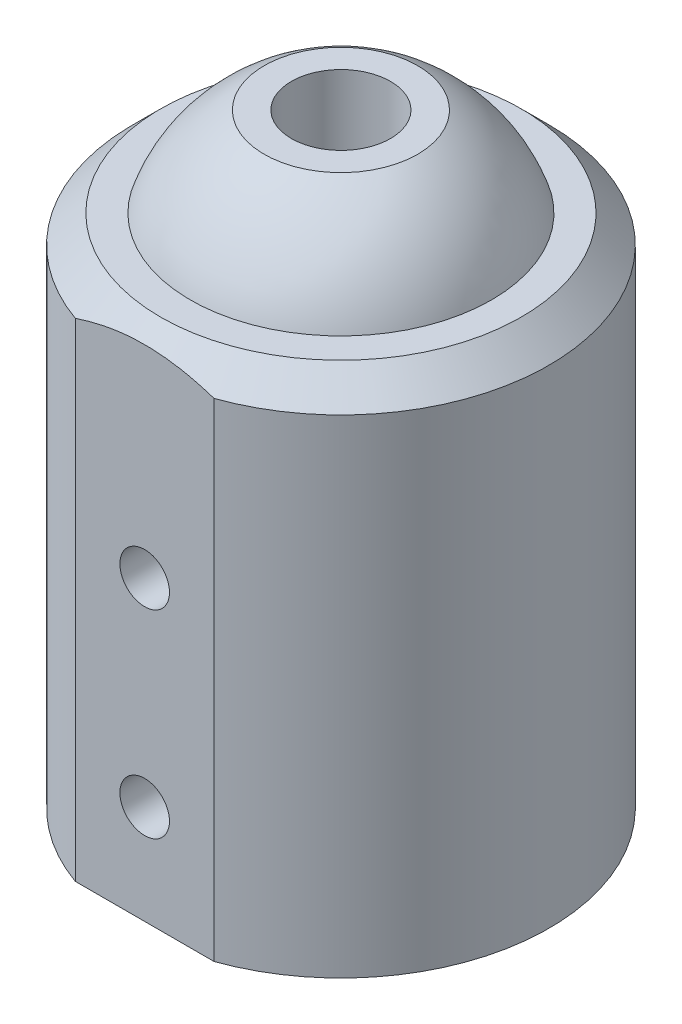
SolidWorks part; units mm, degrees
material "201 退火不锈钢 (SS)"
ref_plane "前视基准面" through (0, 0, 0) normal (0, 0, 1) x (1, 0, 0)
ref_plane "上视基准面" through (0, 0, 0) normal (0, 1, 0) x (1, 0, 0)
ref_plane "右视基准面" through (0, 0, 0) normal (1, 0, 0) x (0, 0, -1)
other "Configuration Table"
sketch "草图1" plane through (0, 0, 0) normal (0, 0, 1) x (1, 0, 0)
  line L0 (0, 33.5828) -> (0, -10.2614) construction
  line L1 (0, 0) -> (10.5, 0)
  line L4 (10.5, 0) -> (10.5, 24.5993)
  line L5 (10.5, 24.5993) -> (9.0993, 26)
  line L6 (9.0993, 26) -> (7.5993, 26)
  line L7 (0, 30.5) -> (3.873, 30.5)
  line L8 (0, 0) -> (0, 30.5)
  arc A1 (7.5993, 26) -> (3.873, 30.5) centre (0, 23.5) ccw
  dimension "D1" = 10.5
  dimension "D4" = 16
  dimension "D2" = 23.5
  dimension "D3" = 4.5
  dimension "D5" = 7
  dimension "D7" = 135
  dimension "D8" = 1.5
revolve "旋转1" add sketch "草图1" angle 360 about L0
sketch "草图2" plane through (0, 30.5, 0) normal (0, 1, 0) x (1, 0, 0)
  circle A0 centre (0, 0) radius 2.5
  dimension "D1" = 5
extrude "切除-拉伸1" cut sketch "草图2" against normal blind 5
cosmetic thread "装饰螺纹线1" parameters "D2"=6
sketch "草图3" plane through (0, 0, 0) normal (0, 1, 0) x (1, 0, 0)
  line L0 (-3.4986, -9.9) -> (3.4986, -9.9)
  circle A8 centre (0, 0) radius 10.5 construction
  circle A9 centre (0, 0) radius 2.5 construction
  arc A10 (-3.4986, -9.9) -> (3.4986, -9.9) centre (0, 0) ccw
  dimension "D1" = 9.9
extrude "切除-拉伸2" cut sketch "草图3" along normal blind 45
sketch "草图4" plane through (0, 0, 9.9) normal (0, 0, 1) x (1, 0, 0)
  line L0 (3.4986, 0) -> (-3.4986, 0) construction
  circle A0 centre (0, 5) radius 1.25
  circle A1 centre (0, 15) radius 1.25
  point P6 (0, 0)
  dimension "D1" = 2.5
  dimension "D2" = 2.5
  dimension "D3" = 5
  dimension "D4" = 10
extrude "切除-拉伸3" cut sketch "草图4" against normal blind 10
